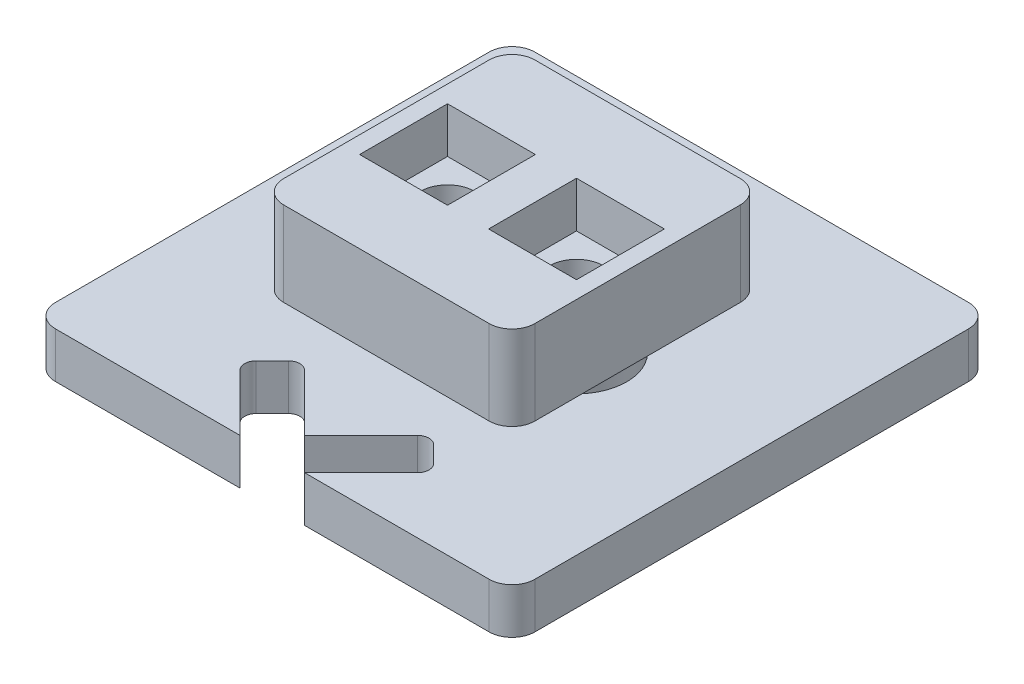
SolidWorks part; units mm, degrees
ref_plane "Front Plane" through (0, 0, 0) normal (0, 0, 1) x (1, 0, 0)
ref_plane "Top Plane" through (0, 0, 0) normal (0, 1, 0) x (1, 0, 0)
ref_plane "Right Plane" through (0, 0, 0) normal (1, 0, 0) x (0, 0, -1)
sketch "Sketch1" plane through (0, 0, 0) normal (0, 1, 0) x (1, 0, 0)
  line L1 (-5.5, -5.5) -> (5.5, -5.5)
  line L2 (-5.5, -5.5) -> (-5.5, 5.5)
  line L3 (-5.5, 5.5) -> (5.5, 5.5)
  line L4 (5.5, -5.5) -> (5.5, 5.5)
  line L5 (-5.5, -5.5) -> (5.5, 5.5) construction
  line L6 (-5.5, 5.5) -> (5.5, -5.5) construction
  point P0 (0, 0)
  dimension "D1" = 11
  dimension "D2" = 11
extrude "Boss-Extrude1" add sketch "Sketch1" along normal blind 3.7
fillet "Fillet1" radius 1 4 edges at (-5.5, 1.85, -5.5) (-5.5, 1.85, 5.5) (5.5, 1.85, -5.5) (5.5, 1.85, 5.5)
sketch "Sketch2" plane through (0, 3.7, 0) normal (0, 1, 0) x (1, 0, 0)
  line L0 (-2.825, 0) -> (2.825, 0) construction
  line L2 (-4.75, -1.925) -> (-0.9, -1.925)
  line L3 (-4.75, -1.925) -> (-4.75, 1.925)
  line L4 (-4.75, 1.925) -> (-0.9, 1.925)
  line L5 (-0.9, -1.925) -> (-0.9, 1.925)
  line L6 (-4.75, -1.925) -> (-0.9, 1.925) construction
  line L7 (-4.75, 1.925) -> (-0.9, -1.925) construction
  line L8 (0.9, -1.925) -> (4.75, -1.925)
  line L9 (0.9, -1.925) -> (0.9, 1.925)
  line L10 (0.9, 1.925) -> (4.75, 1.925)
  line L11 (4.75, -1.925) -> (4.75, 1.925)
  line L12 (0.9, -1.925) -> (4.75, 1.925) construction
  line L13 (0.9, 1.925) -> (4.75, -1.925) construction
  point P4 (0, 0)
  dimension "D1" = 3.85
  dimension "D2" = 3.85
  dimension "D3" = 3.85
  dimension "D4" = 3.85
  dimension "D5" = 5.65
extrude "Cut-Extrude1" cut sketch "Sketch2" against normal blind 2
sketch "Sketch4" plane through (0, 0, 0) normal (0, -1, 0) x (-1, 0, 0)
  line L0 (2.825, 0) -> (-2.825, 0) construction
  circle A0 centre (2.825, 0) radius 2.2
  circle A1 centre (-2.825, 0) radius 2.2
  point P8 (0, 0)
  dimension "D1" = 5.65
  dimension "D2" = 4.4
  dimension "D3" = 4.4
extrude "Boss-Extrude2" add sketch "Sketch4" along normal blind 3
sketch "Sketch5" plane through (0, -3, 0) normal (0, -1, 0) x (-1, 0, 0)
  line L1 (9.5, 10.5) -> (-9.5, 10.5)
  line L2 (10.5, 9.5) -> (10.5, -9.5)
  line L3 (9.5, -10.5) -> (-9.5, -10.5)
  line L4 (-10.5, 9.5) -> (-10.5, -9.5)
  line L5 (10.5, 10.5) -> (-10.5, -10.5) construction
  line L6 (10.5, -10.5) -> (-10.5, 10.5) construction
  arc A0 (10.5, -9.5) -> (9.5, -10.5) centre (9.5, -9.5) cw
  arc A1 (-10.5, -9.5) -> (-9.5, -10.5) centre (-9.5, -9.5) ccw
  arc A2 (-9.5, 10.5) -> (-10.5, 9.5) centre (-9.5, 9.5) ccw
  arc A3 (9.5, 10.5) -> (10.5, 9.5) centre (9.5, 9.5) cw
  point P0 (0, 0)
  dimension "D3" = 1
  dimension "D1" = 21
  dimension "D2" = 21
extrude "Boss-Extrude3" add sketch "Sketch5" against normal blind 2
sketch "Sketch3" plane through (0, 3.7, 0) normal (0, 1, 0) x (1, 0, 0)
  line L0 (-2.825, 0) -> (2.825, 0) construction
  circle A0 centre (-2.825, 0) radius 1.2
  circle A1 centre (2.825, 0) radius 1.2
  point P8 (0, 0)
  dimension "D2" = 2.4
  dimension "D3" = 2.4
  dimension "D1" = 5.65
extrude "Cut-Extrude2" cut sketch "Sketch3" against normal through all
sketch "Sketch7" plane through (0, -1, 0) normal (0, 1, 0) x (1, 0, 0)
  line L0 (9.5, -10.5) -> (-9.5, -10.5) construction
  line L1 (2.8284, -14.7426) -> (4.2426, -13.3284)
  line L2 (2.8284, -14.7426) -> (-3.8891, -8.0251)
  line L3 (-3.8891, -7.318) -> (-3.182, -6.6109)
  line L4 (4.2426, -13.3284) -> (-2.4749, -6.6109)
  line L5 (2.8284, -14.7426) -> (-2.8284, -6.2574) construction
  line L6 (-4.2426, -7.6716) -> (4.2426, -13.3284) construction
  line L8 (-4.2426, -13.3284) -> (-2.8284, -14.7426)
  line L9 (-4.2426, -13.3284) -> (2.4749, -6.6109)
  line L10 (3.182, -6.6109) -> (3.8891, -7.318)
  line L11 (-2.8284, -14.7426) -> (3.8891, -8.0251)
  line L12 (-4.2426, -13.3284) -> (4.2426, -7.6716) construction
  line L13 (2.8284, -6.2574) -> (-2.8284, -14.7426) construction
  arc A0 (-2.4749, -6.6109) -> (-3.182, -6.6109) centre (-2.8284, -6.9645) ccw
  arc A1 (3.8891, -7.318) -> (3.8891, -8.0251) centre (3.5355, -7.6716) cw
  arc A2 (3.182, -6.6109) -> (2.4749, -6.6109) centre (2.8284, -6.9645) ccw
  arc A3 (-3.8891, -7.318) -> (-3.8891, -8.0251) centre (-3.5355, -7.6716) ccw
  point P0 (0, -10.5)
  point P7 (0, -10.5)
  point P12 (-1.4142, -10.5)
  point P13 (1.4142, -10.5)
  line M12 (-9.5, -10.5) -> (9.5, -10.5)
  dimension "D7" = 0.5
  dimension "D8" = 0.5
  dimension "D1" = 2
  dimension "D2" = 45
  dimension "D3" = 2
  dimension "D4" = 45
  dimension "D5" = 4
  dimension "D6" = 4
extrude "Cut-Extrude3" cut sketch "Sketch7" against normal through all contours L10 A2 L9 L4 L11 A1 | L3 A3 L2 L9 L4 A0 | L9 L4 M12
sketch "Sketch8" plane through (0, -3, 0) normal (0, -1, 0) x (1, 0, 0)
  circle A0 centre (-2.825, 0) radius 1.2
  circle A1 centre (-2.825, 0) radius 2.2
  circle A2 centre (2.825, 0) radius 1.2
  circle A3 centre (2.825, 0) radius 2.2
  dimension "D1" = 1
  dimension "D2" = 1
extrude "Boss-Extrude4" add sketch "Sketch8" along normal blind 4
equation "\"D2@Sketch2\"=\"D1@Sketch2\""
equation "\"D3@Sketch2\"=\"D1@Sketch2\""
equation "\"D4@Sketch2\"=\"D1@Sketch2\""
equation "\"D2@Sketch1\"=\"D1@Sketch1\""
equation "\"D3@Sketch3\"=\"D2@Sketch3\""
equation "\"D3@Sketch4\"=\"D2@Sketch4\""
equation "\"D2@Sketch5\"=\"D1@Sketch5\""
equation "\"D3@Sketch7\"=\"D1@Sketch7\""
equation "\"D6@Sketch7\"=\"D5@Sketch7\""
equation "\"D2@Sketch8\"=\"D1@Sketch8\""
